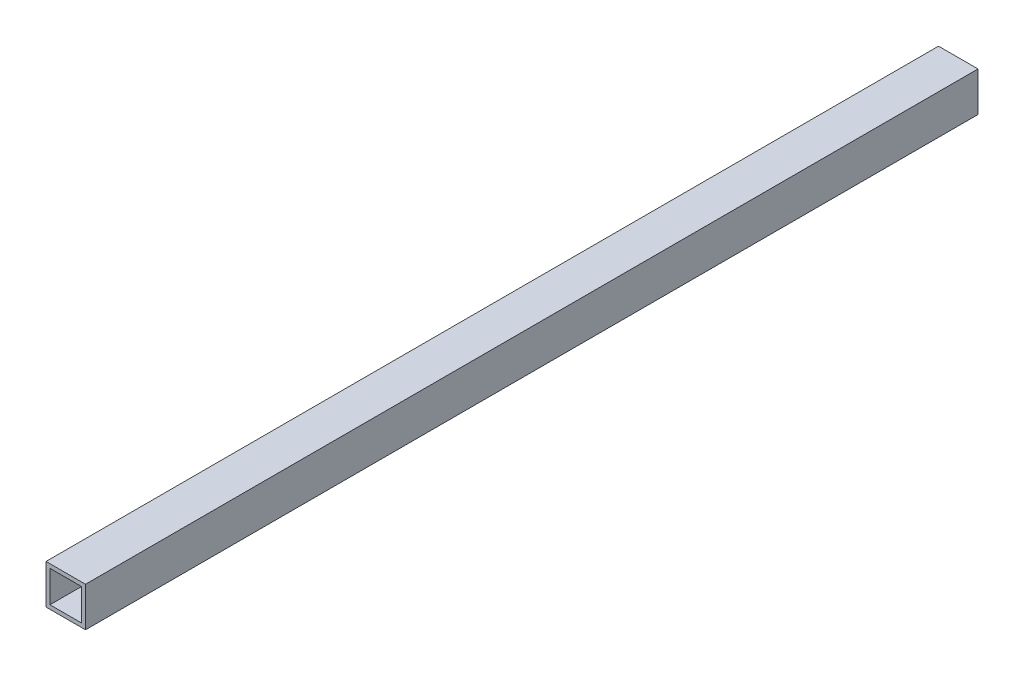
SolidWorks part; units mm, degrees
material "Aleación 1060"
ref_plane "Alzado" through (0, 0, 0) normal (0, 0, 1) x (1, 0, 0)
ref_plane "Planta" through (0, 0, 0) normal (0, 1, 0) x (1, 0, 0)
ref_plane "Vista lateral" through (0, 0, 0) normal (1, 0, 0) x (0, 0, -1)
sketch "Croquis1" plane through (0, 0, 0) normal (0, 0, 1) x (1, 0, 0)
  line L0 (-8, 8) -> (-8, -8)
  line L1 (-10, 10) -> (10, 10)
  line L2 (-10, 10) -> (-10, -10)
  line L3 (-10, -10) -> (10, -10)
  line L4 (10, 10) -> (10, -10)
  line L5 (-8, -8) -> (8, -8)
  line L6 (8, 8) -> (8, -8)
  line L7 (-8, 8) -> (8, 8)
  point P4 (0, 10)
  point P6 (10, 0)
  dimension "D1" = 20
  dimension "D2" = 20
  dimension "D3" = 2
extrude "Saliente-Extruir1" add sketch "Croquis1" along normal mid plane 452
